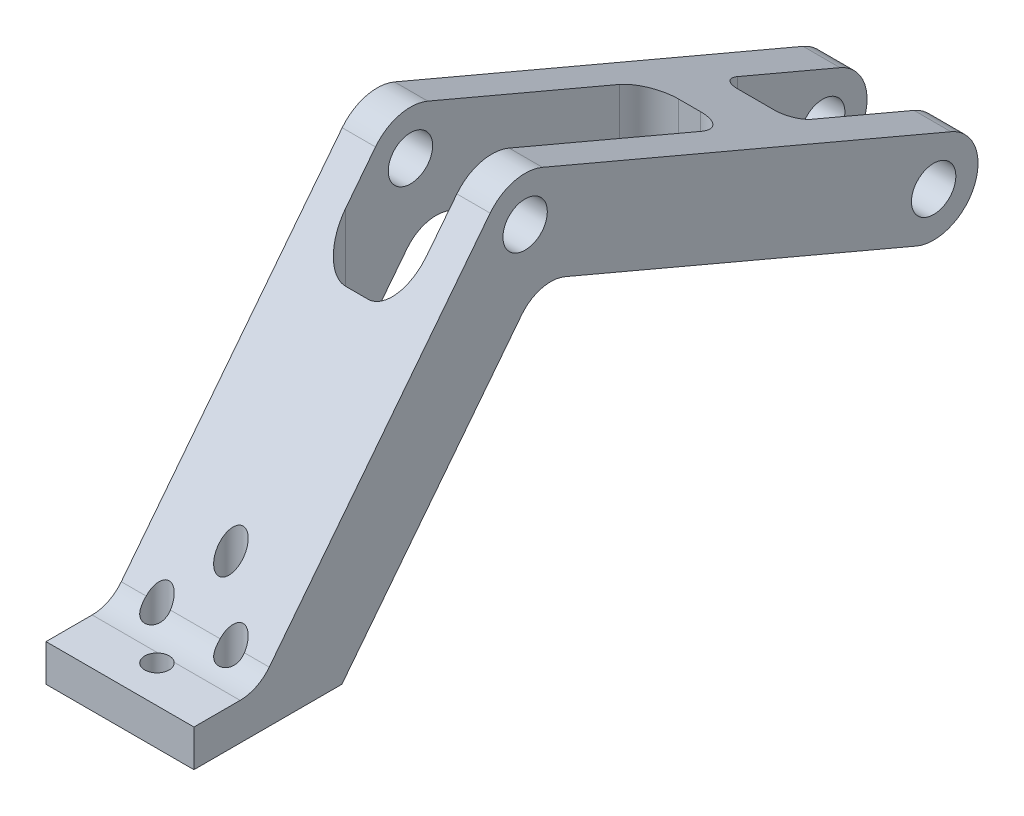
SolidWorks part; units mm, degrees
material "ASTM A36 Aço"
ref_plane "Plano frontal" through (0, 0, 0) normal (0, 0, 1) x (1, 0, 0)
ref_plane "Plano superior" through (0, 0, 0) normal (0, 1, 0) x (1, 0, 0)
ref_plane "Plano direito" through (0, 0, 0) normal (1, 0, 0) x (0, 0, -1)
sketch "Esboço1" plane through (0, 0, 0) normal (1, 0, 0) x (0, 0, -1)
  line L0 (0, 0) -> (0, 5)
  line L1 (0, 5) -> (6.2395, 5)
  line L2 (10.1794, 6.9215) -> (40.0431, 45.1411)
  line L4 (47.1157, 46.9697) -> (102.3447, 23.5229)
  line L5 (97.6553, 12.4771) -> (50.1957, 32.6255)
  line L6 (44.3019, 31.1016) -> (20, 0)
  line L7 (20, 0) -> (0, 0)
  line L8 (44.771, 41.4468) -> (100, 18) construction
  arc A0 (40.0431, 45.1411) -> (47.1157, 46.9697) centre (44.771, 41.4468) cw
  arc A1 (102.3447, 23.5229) -> (97.6553, 12.4771) centre (100, 18) cw
  circle A2 centre (44.771, 41.4468) radius 3
  circle A3 centre (100, 18) radius 3
  arc A4 (50.1957, 32.6255) -> (44.3019, 31.1016) centre (48.2418, 28.0231) ccw
  arc A5 (6.2395, 5) -> (10.1794, 6.9215) centre (6.2395, 10) ccw
  point P6 (0, 0)
  dimension "D4" = 6
  dimension "D5" = 6
  dimension "D8" = 6
  dimension "D10" = 5
  dimension "D1" = 5
  dimension "D2" = 12
  dimension "D3" = 20
  dimension "D6" = 100
  dimension "D7" = 60
  dimension "D9" = 18
  dimension "D11" = 75
extrude "Ressalto-extrusão1" add sketch "Esboço1" along normal blind 20
hole_wizard "Broca de rosquear para tarraxa de M42" positions "Esboço8" profile "Esboço9" hole size "M4" standard "ISO" end condition through all
sketch "Esboço8" plane through (0, 0, 0) normal (0, -1, 0) x (-1, 0, 0)
  line L0 (-20, 0) -> (-20, 20) construction
  line L1 (-20, 20) -> (0, 20) construction
  point P0 (-10, 15)
  point P2 (-10, 5)
  point P4 (-5, 10)
  point P6 (-15, 10)
  point P13 (-15, 10)
  point P14 (-10, 15)
  dimension "D1" = 5
  dimension "D2" = 5
  dimension "D3" = 5
  dimension "D4" = 5
  dimension "D5" = 5
  dimension "D6" = 5
  dimension "D7" = 5
  dimension "D8" = 5
sketch "Esboço9" plane through (10, 0, -15) normal (1, 0, 0) x (0, 0, -1)
  line L0 (0, 0) -> (0, 47.4468)
  line L1 (0, 47.4468) -> (1.65, 47.4468)
  line L2 (1.65, 47.4468) -> (1.65, 0)
  line L5 (1.65, 0) -> (0, 0)
  line L11 (0, -6.35) -> (0, 107.95) construction
  dimension "Thru Hole Dia." = 3.3
  dimension "Thru Hole Depth" = 47.4468
sketch "Esboço10" plane through (0, 0, 0) normal (0, 1, 0) x (1, 0, 0)
  line L0 (4.5, 36) -> (4.5, 73)
  line L1 (8.5, 77) -> (11.5, 77)
  line L2 (15.5, 73) -> (15.5, 36)
  line L3 (11.5, 32) -> (8.5, 32)
  line L4 (20, 20) -> (0, 20) construction
  line L5 (20, 0) -> (0, 0) construction
  arc A0 (8.5, 77) -> (4.5, 73) centre (8.5, 73) ccw
  arc A1 (15.5, 73) -> (11.5, 77) centre (11.5, 73) ccw
  arc A2 (15.5, 36) -> (11.5, 32) centre (11.5, 36) cw
  arc A3 (8.5, 32) -> (4.5, 36) centre (8.5, 36) cw
  point P16 (10, 0)
  point P17 (10, 32)
  dimension "D2" = 4
  dimension "D1" = 12
  dimension "D3" = 11
  dimension "D4" = 45
extrude "Corte-extrusão1" cut sketch "Esboço10" along normal blind 50
sketch "Esboço11" plane through (0, 0, 0) normal (0, 1, 0) x (1, 0, 0)
  line L0 (5, 106) -> (5, 88.5)
  line L1 (20, 106) -> (0, 106) construction
  line L2 (7.5, 86) -> (12.5, 86)
  line L3 (15, 88.5) -> (15, 106)
  line L4 (5, 106) -> (15, 106)
  line L5 (20, 97.6553) -> (20, 106) construction
  arc A0 (12.5, 86) -> (15, 88.5) centre (12.5, 88.5) ccw
  arc A1 (7.5, 86) -> (5, 88.5) centre (7.5, 88.5) cw
  point P8 (15, 86)
  point P11 (5, 86)
  point P12 (0, 0)
  point P13 (13.9759, 106)
  point P14 (32.5227, 106)
  point P15 (3.3323, 106)
  point P16 (0, 0)
  dimension "D3" = 2.5
  dimension "D1" = 20
  dimension "D2" = 10
  dimension "D4" = 5
extrude "Corte-extrusão2" cut sketch "Esboço11" along normal blind 50
